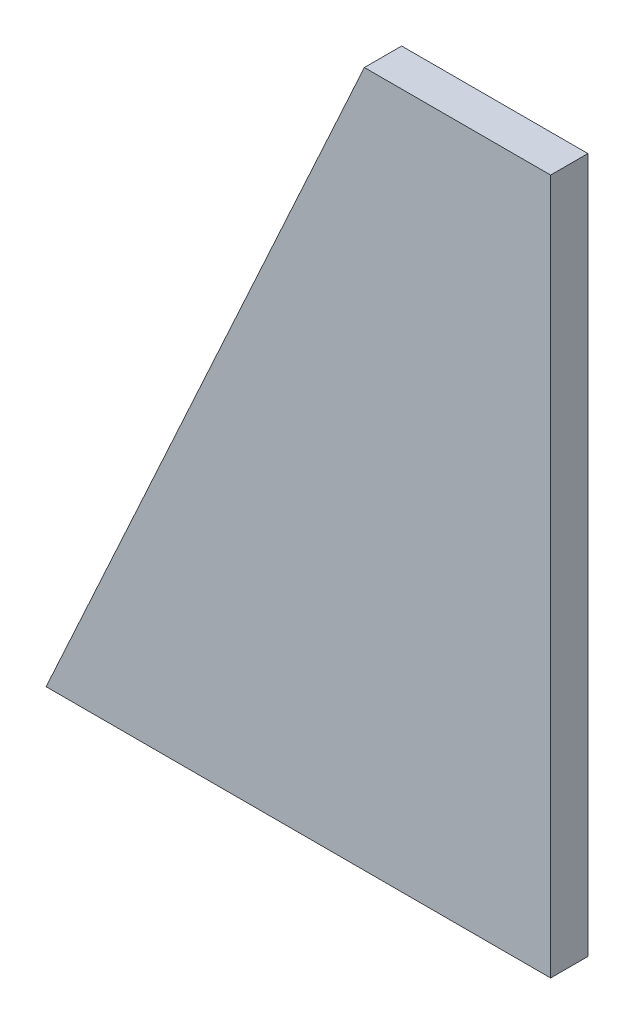
SolidWorks part; units mm, degrees
material "AISI 4340 Aço, normalizado"
ref_plane "Plano frontal" through (0, 0, 0) normal (0, 0, 1) x (1, 0, 0)
ref_plane "Plano superior" through (0, 0, 0) normal (0, 1, 0) x (1, 0, 0)
ref_plane "Plano direito" through (0, 0, 0) normal (1, 0, 0) x (0, 0, -1)
sketch "Esboço1" plane through (0, 0, 0) normal (0, 0, 1) x (1, 0, 0)
  line L0 (0, 0) -> (0, 56)
  line L1 (0, 56) -> (-15, 56)
  line L2 (-15, 56) -> (-40.63, 0)
  line L3 (-40.63, 0) -> (0, 0)
  dimension "D1" = 24.593
  dimension "D2" = 15
  dimension "D3" = 56
extrude "Ressalto-extrusão1" add sketch "Esboço1" along normal blind 3
